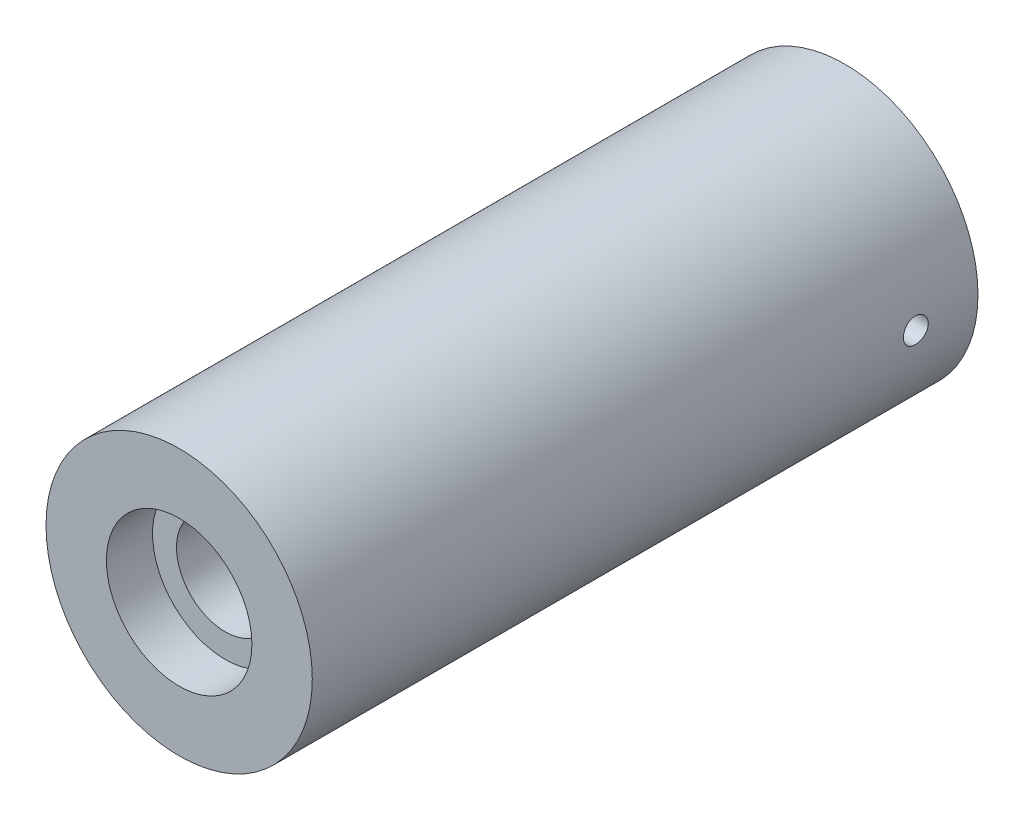
SolidWorks part; units mm, degrees
ref_plane "Front Plane" through (0, 0, 0) normal (0, 0, 1) x (1, 0, 0)
ref_plane "Top Plane" through (0, 0, 0) normal (0, 1, 0) x (1, 0, 0)
ref_plane "Right Plane" through (0, 0, 0) normal (1, 0, 0) x (0, 0, -1)
sketch "Sketch1" plane through (0, 0, 0) normal (0, 0, 1) x (1, 0, 0)
  circle A0 centre (0, 0) radius 15
  dimension "D1" = 30
extrude "Boss-Extrude1" add sketch "Sketch1" along normal blind 75
sketch "Sketch2" plane through (0, 0, 75) normal (0, 0, 1) x (1, 0, 0)
  circle A0 centre (0, 0) radius 8.2
  dimension "D1" = 16.4
extrude "Cut-Extrude1" cut sketch "Sketch2" against normal blind 5.2
sketch "Sketch3" plane through (0, 0, 0) normal (0, 0, -1) x (-1, 0, 0)
  line L0 (-2.25, 1.0897) -> (-2.25, -1.0897)
  arc A0 (-2.25, -1.0897) -> (-2.25, 1.0897) centre (0, 0) ccw
  dimension "D1" = 5
  dimension "D2" = 2.25
extrude "Cut-Extrude2" cut sketch "Sketch3" against normal blind 25
ref_plane "Plane2" through (15, 0, 0) normal (1, 0, 0) x (0, 0, -1)
sketch "Sketch5" plane through (15, 0, 0) normal (1, 0, 0) x (0, 0, -1)
  line L0 (-95.905, 0) -> (5.9386, 0) construction
  line L1 (-7, 15) -> (-7, -15) construction
  line L2 (0, 15) -> (-75, 15) construction
  line L3 (-75, -15) -> (0, -15) construction
  line L4 (0, -15) -> (0, 15) construction
  circle A0 centre (-7, 0) radius 1.4
  dimension "D2" = 2.8
  dimension "D1" = 7
extrude "Cut-Extrude4" cut sketch "Sketch5" against normal blind 14
sketch "Sketch6" plane through (0, 0, 69.8) normal (0, 0, 1) x (1, 0, 0)
  circle A0 centre (0, 0) radius 5.5
  dimension "D1" = 11
extrude "Cut-Extrude5" cut sketch "Sketch6" against normal blind 25
sketch "Sketch8" plane through (0, 0, 0) normal (0, 0, -1) x (-1, 0, 0)
  line L0 (-2.25, 1.0897) -> (-2.25, -1.0897)
  arc A0 (-2.25, 1.0897) -> (-2.25, -1.0897) centre (0, 0) ccw
extrude "Cut-Extrude6" cut sketch "Sketch8" against normal blind 10
equation "\"m4\"= 4.3"
equation "\"shaft hole\"= 5.5"
equation "\"tightener\"= 2.8"
